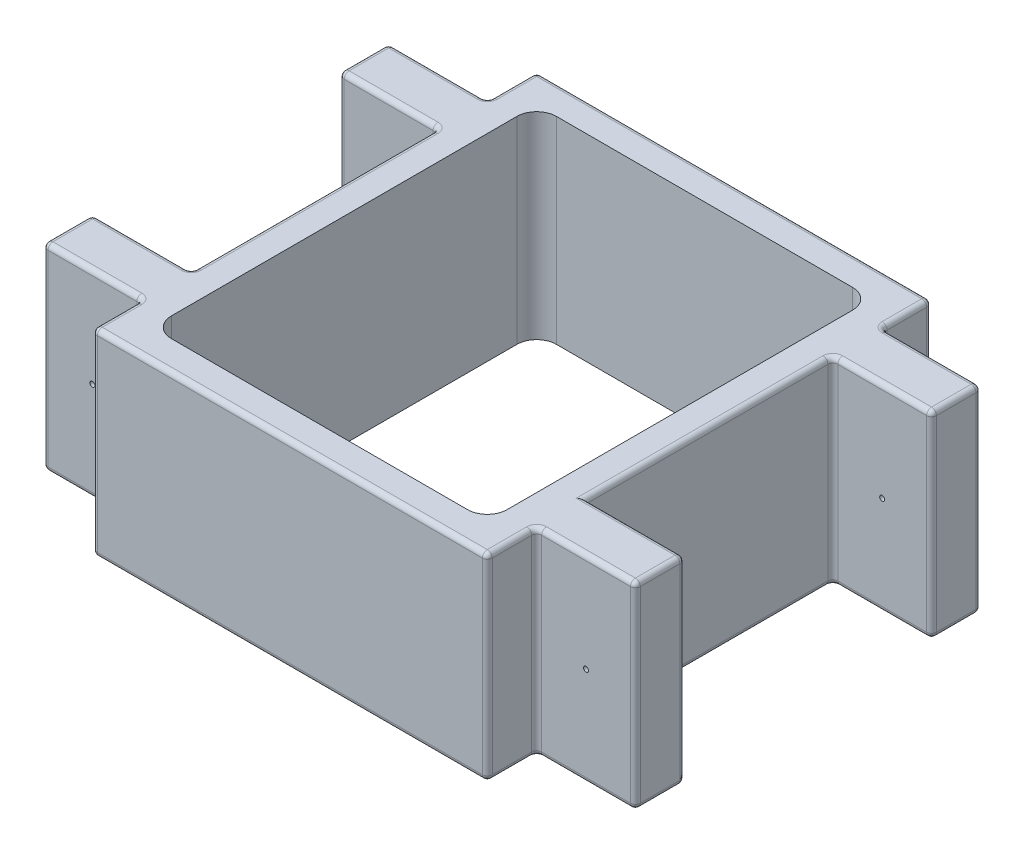
SolidWorks part; units mm, degrees
ref_plane "Alzado" through (0, 0, 0) normal (0, 0, 1) x (1, 0, 0)
ref_plane "Planta" through (0, 0, 0) normal (0, 1, 0) x (1, 0, 0)
ref_plane "Vista lateral" through (0, 0, 0) normal (1, 0, 0) x (0, 0, -1)
sketch "Croquis1" plane through (0, 0, 0) normal (0, 1, 0) x (1, 0, 0)
  line L0 (0, -2.25) -> (0, 2.25)
  line L1 (0, 2.25) -> (-2, 2.25)
  line L2 (-2, 2.25) -> (-2, 1.75)
  line L3 (-2, 1.75) -> (-3, 1.75)
  line L4 (-3, 1.75) -> (-3, 1.25)
  line L5 (-3, 1.25) -> (-2, 1.25)
  line L6 (-2, 1.25) -> (-2, -1.25)
  line L7 (-2, -1.25) -> (-3, -1.25)
  line L8 (-3, -1.25) -> (-3, -1.75)
  line L9 (-3, -1.75) -> (-2, -1.75)
  line L10 (-2, -1.75) -> (-2, -2.25)
  line L11 (-2, -2.25) -> (0, -2.25)
  dimension "D1" = 2.25
  dimension "D2" = 2.25
  dimension "D3" = 0.5
  dimension "D4" = 0.5
  dimension "D5" = 1
  dimension "D6" = 1
  dimension "D7" = 2
  dimension "D8" = 2
  dimension "D9" = 2
  dimension "D10" = 0.5
  dimension "D11" = 0.5
extrude "Saliente-Extruir1" add sketch "Croquis1" along normal blind 2
sketch "Croquis2" plane through (0, 0, 1.75) normal (0, 0, 1) x (1, 0, 0)
  line L0 (-2, 2) -> (-2, 0) construction
  line L1 (-3, 0) -> (-2, 0) construction
  circle A0 centre (-2.5, 1) radius 0.025
  dimension "D1" = 0.05
  dimension "D2" = 0.5
  dimension "D3" = 1
extrude "Cortar-Extruir1" cut sketch "Croquis2" against normal through all
mirror "Simetría1" about plane through (0, 0, 0) normal (1, 0, 0) of "Cortar-Extruir1", "Saliente-Extruir1"
fillet "Redondeo1" radius 0.05 59 edges at (-2.5, 0, -1.75) (-2.5, 0, -1.25) (-2.5, 0, 1.25) (-2.5, 0, 1.75) (-2, 0, 2) (2, 0, 2) (2, 2, 2) (2.5, 0, 1.75) (2.5, 2, 1.75) (2.5, 0, 1.25) (2.5, 2, 1.25) (2, 0, 0) (2, 2, 0) (2.5, 0, -1.25) (2.5, 2, -1.25) (2.5, 0, -1.75) (2.5, 2, -1.75) (2, 0, -2) (2, 2, -2) (0, 0, -2.25) (-3, 1, 1.25) (-3, 1, 1.75) (-3, 0, 1.5) (-2, 1, -1.25) (-2, 1, 1.25) (-2, 0, 0) (-3, 1, -1.75) (-3, 1, -1.25) (-3, 0, -1.5) (-2, 1, -2.25) (-2, 1, -1.75) (-2, 0, -2) (3, 1, -1.25) (3, 1, -1.75) (3, 0, -1.5) (3, 2, -1.5) (3, 1, 1.75) (3, 1, 1.25) (3, 0, 1.5) (3, 2, 1.5) (-2, 1, 2.25) (2, 1, 2.25) (0, 0, 2.25) (0, 2, 2.25) (-2, 2, 2) (-2.5, 2, 1.75) (-3, 2, 1.5) (-2.5, 2, 1.25) (-2, 2, 0) (-2.5, 2, -1.25) (-3, 2, -1.5) (-2.5, 2, -1.75) (-2, 2, -2) (0, 2, -2.25) (2, 1, -2.25) (2, 1, -1.75) (-2, 1, 1.75) (2, 1, 1.75) (2, 1, -1.25)
sketch "Croquis3" plane through (0, 2, 0) normal (0, 1, 0) x (1, 0, 0)
  line L1 (1.5, 1.95) -> (-1.5, 1.95)
  line L2 (1.7, 1.75) -> (1.7, -1.75)
  line L3 (1.5, -1.95) -> (-1.5, -1.95)
  line L4 (-1.7, 1.75) -> (-1.7, -1.75)
  line L5 (1.7, 1.95) -> (-1.7, -1.95) construction
  line L6 (1.7, -1.95) -> (-1.7, 1.95) construction
  arc A0 (-1.5, -1.95) -> (-1.7, -1.75) centre (-1.5, -1.75) cw
  arc A1 (1.7, -1.75) -> (1.5, -1.95) centre (1.5, -1.75) cw
  arc A2 (1.5, 1.95) -> (1.7, 1.75) centre (1.5, 1.75) cw
  arc A3 (-1.5, 1.95) -> (-1.7, 1.75) centre (-1.5, 1.75) ccw
  point P0 (0, 0)
  dimension "D1" = 0.2
  dimension "D2" = 3
  dimension "D3" = 3.5
extrude "Cortar-Extruir2" cut sketch "Croquis3" against normal through all
